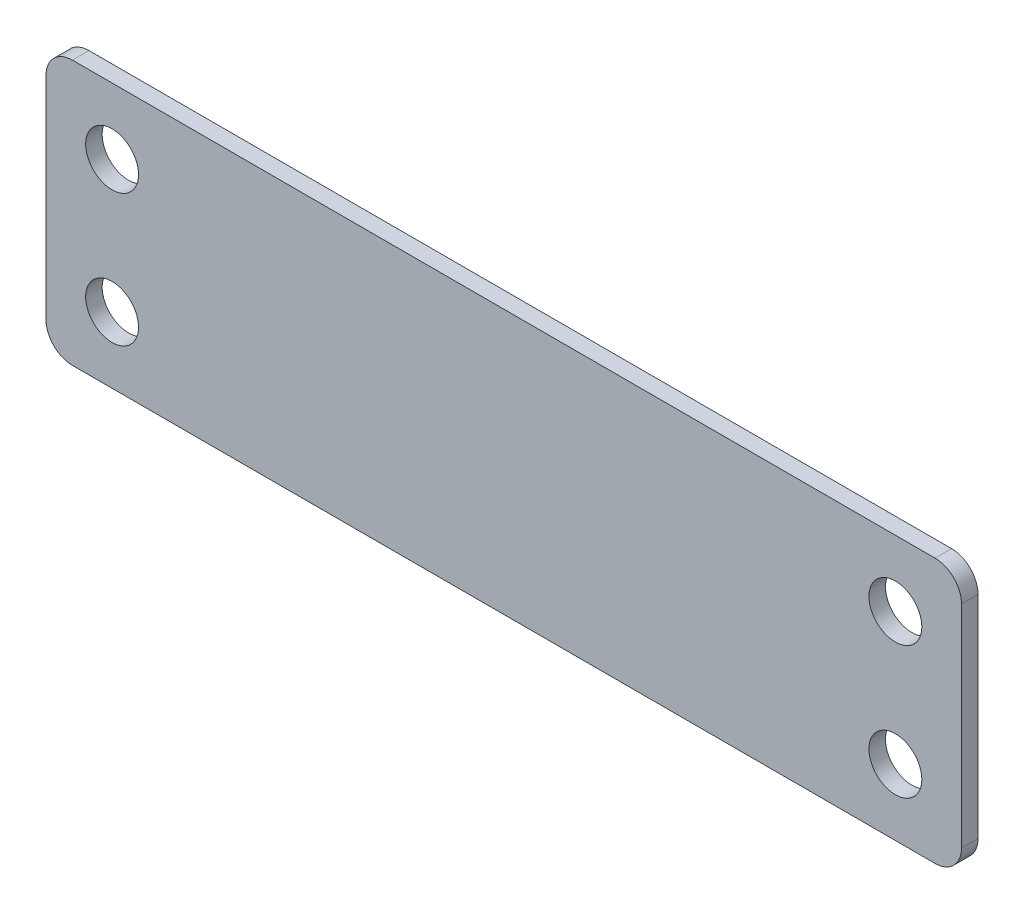
SolidWorks part; units mm, degrees
ref_plane "Front Plane" through (0, 0, 0) normal (0, 0, 1) x (1, 0, 0)
ref_plane "Top Plane" through (0, 0, 0) normal (0, 1, 0) x (1, 0, 0)
ref_plane "Right Plane" through (0, 0, 0) normal (1, 0, 0) x (0, 0, -1)
sketch "Sketch1" plane through (0, 0, 0) normal (0, 0, 1) x (1, 0, 0)
  line L1 (0, 0) -> (-87.95, 0)
  line L2 (0, 0) -> (0, 25.4)
  line L3 (0, 25.4) -> (-87.95, 25.4)
  line L4 (-87.95, 0) -> (-87.95, 25.4)
  dimension "D1" = 25.4
  dimension "D2" = 87.95
extrude "Boss-Extrude1" add sketch "Sketch1" along normal blind 1.5875
fillet "Fillet1" radius 2.54 4 edges at (-87.95, 0, 0.7937) (0, 0, 0.7937) (0, 25.4, 0.7937) (-87.95, 25.4, 0.7937)
sketch "Sketch2" plane through (0, 0, 1.5875) normal (0, 0, 1) x (1, 0, 0)
  line L0 (0, 2.54) -> (0, 22.86) construction
  line L1 (-85.41, 0) -> (-2.54, 0) construction
  line L2 (-2.54, 25.4) -> (-85.41, 25.4) construction
  line L3 (-87.95, 22.86) -> (-87.95, 2.54) construction
  circle A0 centre (-81.6, 19.05) radius 2.54
  circle A1 centre (-81.6, 6.35) radius 2.54
  circle A2 centre (-6.35, 19.05) radius 2.54
  circle A3 centre (-6.35, 6.35) radius 2.54
  dimension "D1" = 5.08
  dimension "D2" = 5.08
  dimension "D3" = 5.08
  dimension "D4" = 5.08
  dimension "D5" = 6.35
  dimension "D6" = 6.35
  dimension "D7" = 6.35
  dimension "D8" = 6.35
  dimension "D9" = 6.35
  dimension "D10" = 6.35
  dimension "D11" = 6.35
  dimension "D12" = 6.35
extrude "Cut-Extrude1" cut sketch "Sketch2" against normal blind 2.54
